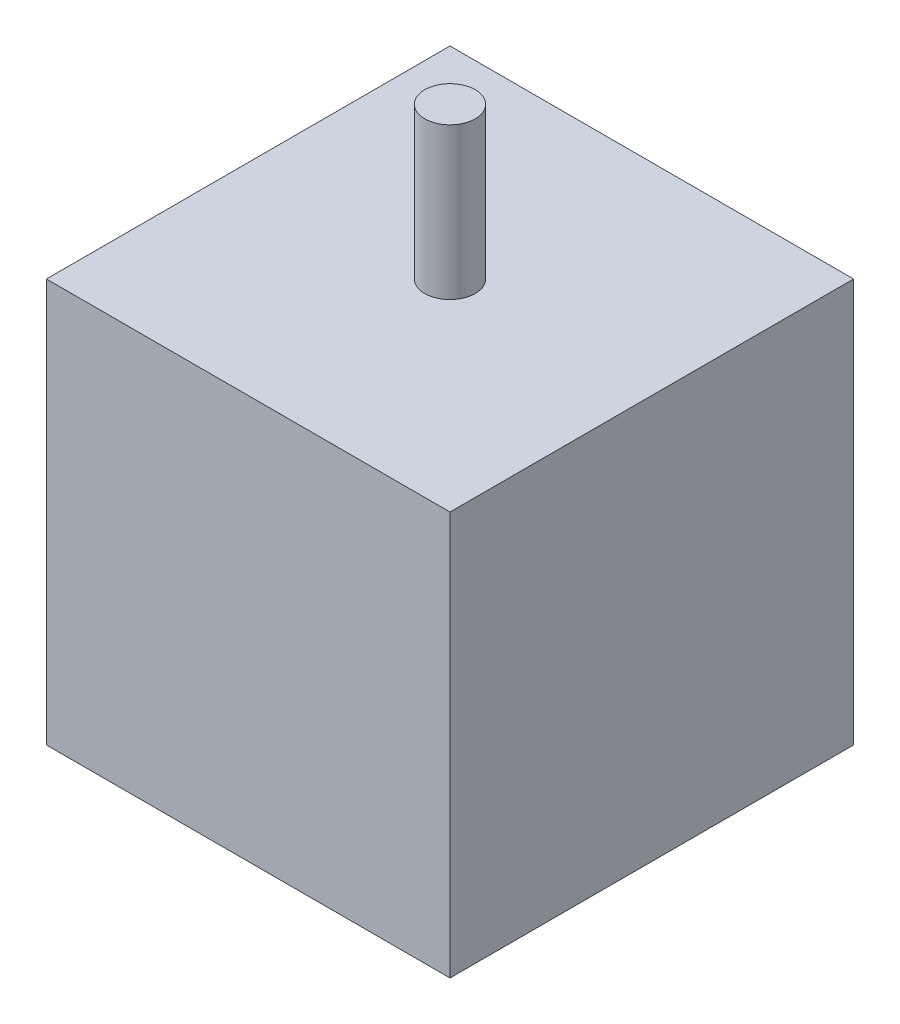
SolidWorks part; units mm, degrees
ref_plane "Front" through (0, 0, 0) normal (0, 0, 1) x (1, 0, 0)
ref_plane "Top" through (0, 0, 0) normal (0, 1, 0) x (1, 0, 0)
ref_plane "Right" through (0, 0, 0) normal (1, 0, 0) x (0, 0, -1)
sketch "Sketch1" plane through (0, 0, 0) normal (0, 1, 0) x (1, 0, 0)
  line L1 (0, 0) -> (101.6, 0)
  line L2 (0, 0) -> (0, 101.6)
  line L3 (0, 101.6) -> (101.6, 101.6)
  line L4 (101.6, 0) -> (101.6, 101.6)
  dimension "D1" = 101.6
extrude "Boss-Extrude1" add sketch "Sketch1" along normal blind 101.6
sketch "Sketch2" plane through (0, 101.6, 0) normal (0, 1, 0) x (1, 0, 0)
  line L0 (0, 50.8) -> (101.6, 50.8) construction
  line L1 (0, 101.6) -> (0, 0) construction
  line L2 (101.6, 0) -> (101.6, 101.6) construction
  circle A0 centre (50.8, 50.8) radius 6.35
  point P8 (0, 0)
  point P9 (0, 0)
  dimension "D1" = 12.7
extrude "Boss-Extrude2" add sketch "Sketch2" along normal blind 38.1
